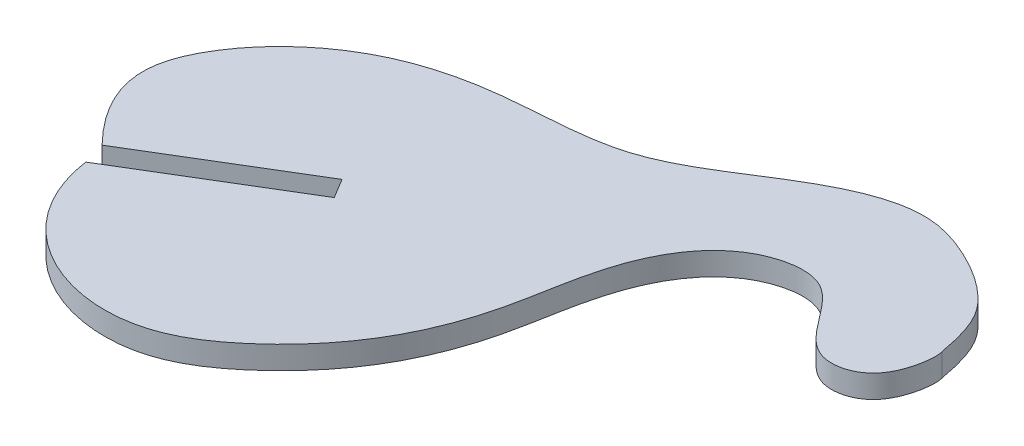
SolidWorks part; units mm, degrees
ref_plane "Спереди" through (0, 0, 0) normal (0, 0, 1) x (1, 0, 0)
ref_plane "Сверху" through (0, 0, 0) normal (0, 1, 0) x (1, 0, 0)
ref_plane "Справа" through (0, 0, 0) normal (1, 0, 0) x (0, 0, -1)
sketch "Эскиз1" plane through (0, 0, 0) normal (0, 1, 0) x (1, 0, 0)
  line L0 (67.558, 140.4457) -> (334.2247, 140.4457) construction
  line L28 (59.352, 27.4921) -> (85.4743, 43.2425)
  line L29 (85.4743, 43.2425) -> (87.5397, 39.817)
  line L30 (87.5397, 39.817) -> (60.4886, 23.5066)
  spline S9 degree 3 poles (163.8264, 69.6022) (162.712, 76.059) (159.4497, 81.2233) (151.425, 86.3412) (141.5269, 89.6263) (125.4118, 84.4426) (109.6744, 70.1141) (87.0869, 70.7587) (67.9818, 65.8519) (52.2594, 51.7852) (49.5652, 37.5209) (59.352, 27.4921) knots 0 0 0 0 0.062137 0.129358 0.186342 0.269917 0.458077 0.600564 0.712354 0.857805 1 1 1 1
  spline S10 degree 3 poles (163.8264, 69.6022) (164.3503, 68.2473) (163.2804, 59.5227) (150.4778, 56.1205) (146.0935, 71.4221) (130.0021, 68.6631) (121.0986, 55.0208) (119.8038, 38.605) (113.6572, 22.5603) (104.1104, 11.0858) (84.5675, -2.3576) (62.8959, 6.9211) (60.4886, 23.5066) knots 0 0 0 0 0.056553 0.10407 0.202496 0.261978 0.363177 0.483727 0.568901 0.679995 0.759059 1 1 1 1
extrude "Бобышка-Вытянуть1" add sketch "Эскиз1" along normal blind 4
